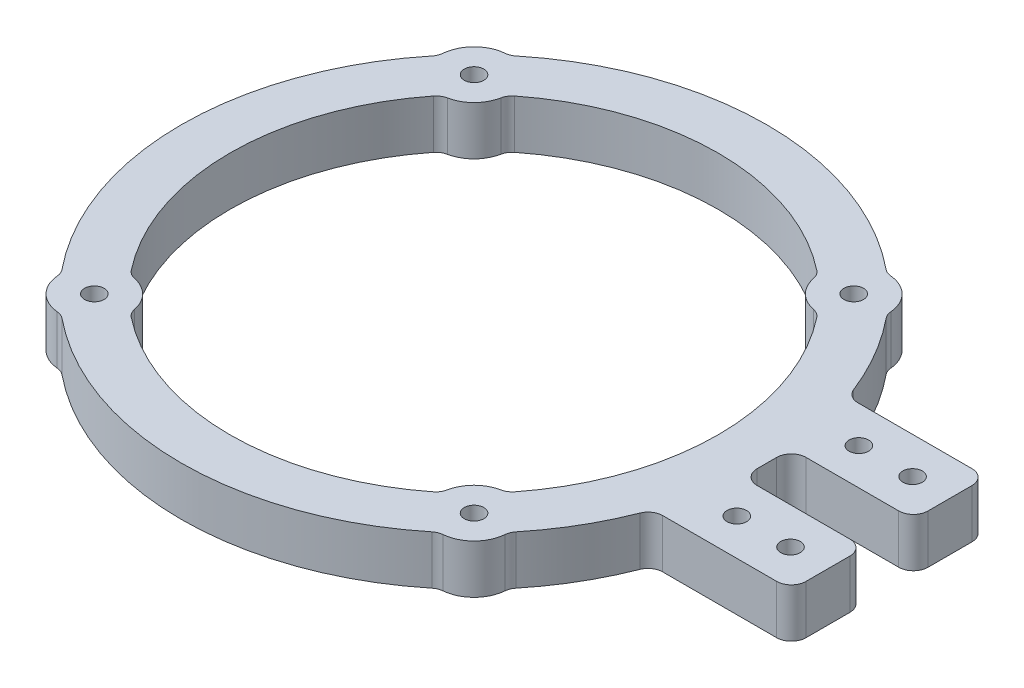
SolidWorks part; units mm, degrees
material "1060 Alloy"
ref_plane "Front Plane" through (0, 0, 0) normal (0, 0, 1) x (1, 0, 0)
ref_plane "Top Plane" through (0, 0, 0) normal (0, 1, 0) x (1, 0, 0)
ref_plane "Right Plane" through (0, 0, 0) normal (1, 0, 0) x (0, 0, -1)
sketch "Sketch1" plane through (0, 0, 0) normal (0, 1, 0) x (1, 0, 0)
  line L0 (0, -50) -> (0, -60) construction
  line L1 (0, 0) -> (0, -50) construction
  line L2 (56.5685, -20) -> (85, -20)
  line L3 (85, -20) -> (85, -5)
  line L4 (85, -5) -> (60, -5)
  line L5 (60, -5) -> (60, 5)
  line L6 (60, 5) -> (85, 5)
  line L7 (85, 5) -> (85, 20)
  line L8 (85, 20) -> (56.5685, 20)
  circle A0 centre (0, 0) radius 50
  circle A1 centre (0, 0) radius 60 construction
  arc A2 (56.5685, 20) -> (56.5685, -20) centre (0, 0) ccw
  dimension "D1" = 100
  dimension "D2" = 10
  dimension "D3" = 10
  dimension "D4" = 15
  dimension "D6" = 25
extrude "Boss-Extrude1" add sketch "Sketch1" along normal blind 10
sketch "Sketch3" plane through (0, 10, 0) normal (0, 1, 0) x (1, 0, 0)
  line L0 (38.8909, 38.8909) -> (38.8909, -38.8909) construction
  line L1 (60, -5) -> (60, 5) construction
  circle A0 centre (0, 0) radius 55 construction
  circle A1 centre (38.8909, -38.8909) radius 7
  circle A2 centre (-38.8909, -38.8909) radius 7
  circle A3 centre (-38.8909, 38.8909) radius 7
  circle A4 centre (38.8909, 38.8909) radius 7
  point P14 (0, 0)
  dimension "D1" = 110
  dimension "D2" = 14
  dimension "D3" = 4
extrude "Boss-Extrude2" add sketch "Sketch3" against normal up to surface (10 mm away) up to face at (57.0711, 0, 0)
sketch "Sketch4" plane through (0, 10, 0) normal (0, 1, 0) x (1, 0, 0)
  circle A0 centre (38.8909, -38.8909) radius 2
  circle A1 centre (-38.8909, -38.8909) radius 2
  circle A2 centre (-38.8909, 38.8909) radius 2
  circle A3 centre (38.8909, 38.8909) radius 2
  point P12 (0, 0)
  dimension "D1" = 4
  dimension "D2" = 4
extrude "Cut-Extrude1" cut sketch "Sketch4" against normal blind 10
fillet "Fillet1" radius 3 24 edges at (85, 5, -20) (85, 5, -5) (85, 5, 5) (85, 5, 20) (31.9018, 5, 38.5003) (38.5003, 5, 31.9018) (38.5003, 5, -31.9018) (31.9018, 5, -38.5003) (-31.9018, 5, -38.5003) (-38.5003, 5, -31.9018) (-38.6573, 5, -45.887) (-45.887, 5, -38.6573) (45.887, 5, -38.6573) (38.6573, 5, -45.887) (-38.5003, 5, 31.9018) (-31.9018, 5, 38.5003) (-45.887, 5, 38.6573) (-38.6573, 5, 45.887) (38.6573, 5, 45.887) (45.887, 5, 38.6573) (56.5685, 5, 20) (56.5685, 5, -20) (60, 5, 5) (60, 5, -5)
sketch "Sketch5" plane through (0, 10, 0) normal (0, 1, 0) x (1, 0, 0)
  line L0 (58.6515, 20) -> (85, 5) construction
  line L1 (85, 20) -> (58.6515, 5) construction
  line L2 (58.6515, 5) -> (85, 5) construction
  line L3 (58.6515, 20) -> (58.6515, 5) construction
  line L4 (66.3258, 12.5) -> (77.3258, 12.5) construction
  line L5 (58.6515, 20) -> (85, 20) construction
  line L6 (85, 20) -> (85, 5) construction
  line L7 (63, 5) -> (82, 5) construction
  line L8 (85, 8) -> (85, 17) construction
  line L9 (58.6515, -5) -> (85, -20) construction
  line L10 (85, -5) -> (58.6515, -20) construction
  line L11 (58.6515, -20) -> (85, -20) construction
  line L12 (58.6515, -5) -> (58.6515, -20) construction
  line L13 (66.3258, -12.5) -> (77.3258, -12.5) construction
  line L14 (58.6515, -5) -> (85, -5) construction
  line L15 (85, -5) -> (85, -20) construction
  line L16 (82, -5) -> (63, -5) construction
  line L17 (58.6515, -20) -> (82, -20) construction
  circle A0 centre (66.3258, 12.5) radius 2
  circle A1 centre (77.3258, 12.5) radius 2
  circle A2 centre (66.3258, -12.5) radius 2
  circle A3 centre (77.3258, -12.5) radius 2
  point P11 (71.8258, 12.5)
  point P21 (71.8258, -12.5)
  dimension "D2" = 4
  dimension "D3" = 4
  dimension "D5" = 4
  dimension "D6" = 4
  dimension "D1" = 11
  dimension "D4" = 11
extrude "Cut-Extrude2" cut sketch "Sketch5" against normal blind 10
